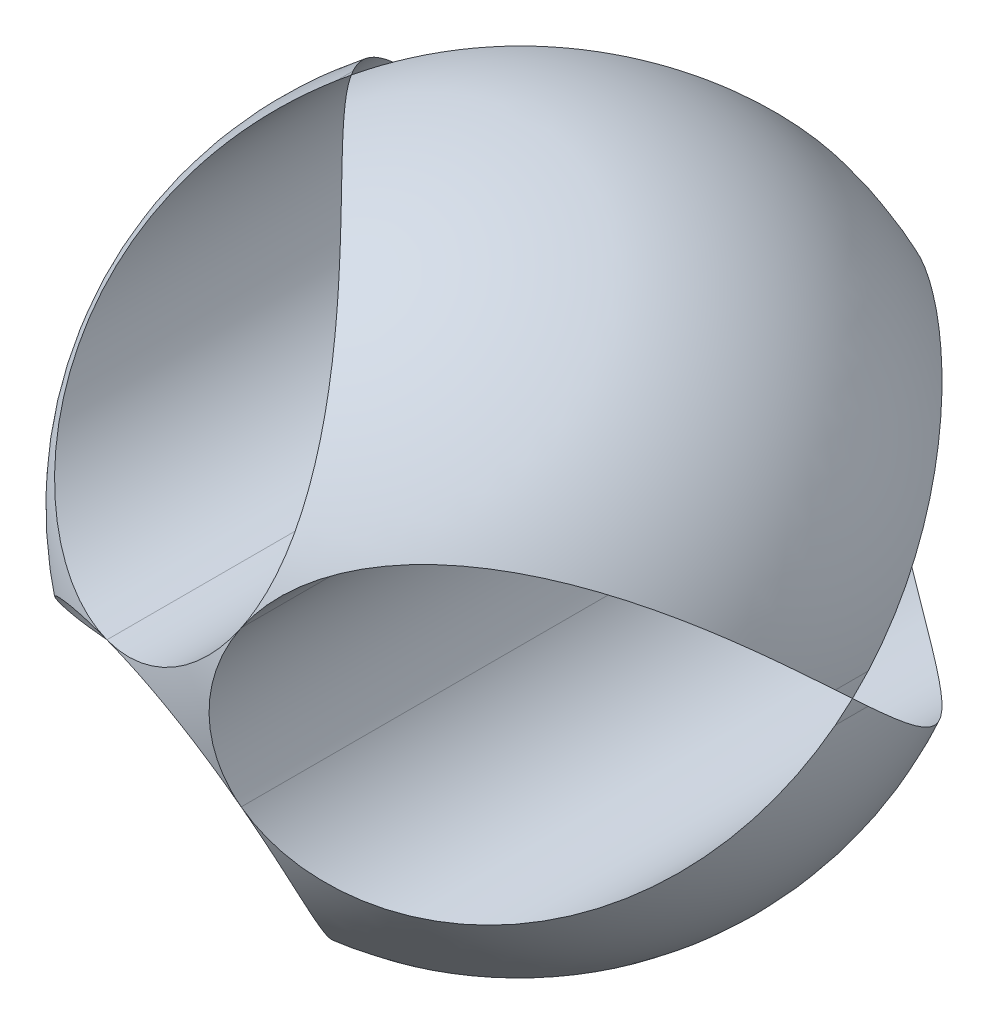
SolidWorks part; units mm, degrees
ref_plane "前视基准面" through (0, 0, 0) normal (0, 0, 1) x (1, 0, 0)
ref_plane "上视基准面" through (0, 0, 0) normal (0, 1, 0) x (1, 0, 0)
ref_plane "右视基准面" through (0, 0, 0) normal (1, 0, 0) x (0, 0, -1)
other "Configuration Table"
sketch "草图2" plane through (0, 0, 0) normal (0, 0, 1) x (1, 0, 0)
  line L0 (0, 0) -> (68.0159, 0) construction
  circle A0 centre (0, 0) radius 30
  circle A1 centre (16.077, 0) radius 13.923
  circle A2 centre (-8.0385, -13.923) radius 13.923
  circle A3 centre (-8.0385, 13.923) radius 13.923
  dimension "D1" = 60
extrude "凸台-拉伸1" add sketch "草图2" along normal mid plane 100
sketch "草图3" plane through (0, 0, 0) normal (1, 0, 0) x (0, 0, -1)
  line L1 (0, 30) -> (0, 36.7586)
  line L2 (0, 36.7586) -> (-96.5977, 36.7586)
  line L3 (-96.5977, 36.7586) -> (-96.5977, -39.9217)
  line L4 (-96.5977, -39.9217) -> (0, -41.4275)
  line L5 (0, -41.4275) -> (0, -30)
  arc A0 (0, 30) -> (0, -30) centre (0, 0) ccw
  dimension "D1" = 60
revolve "切除-旋转2" cut sketch "草图3" angle 360 about L1
